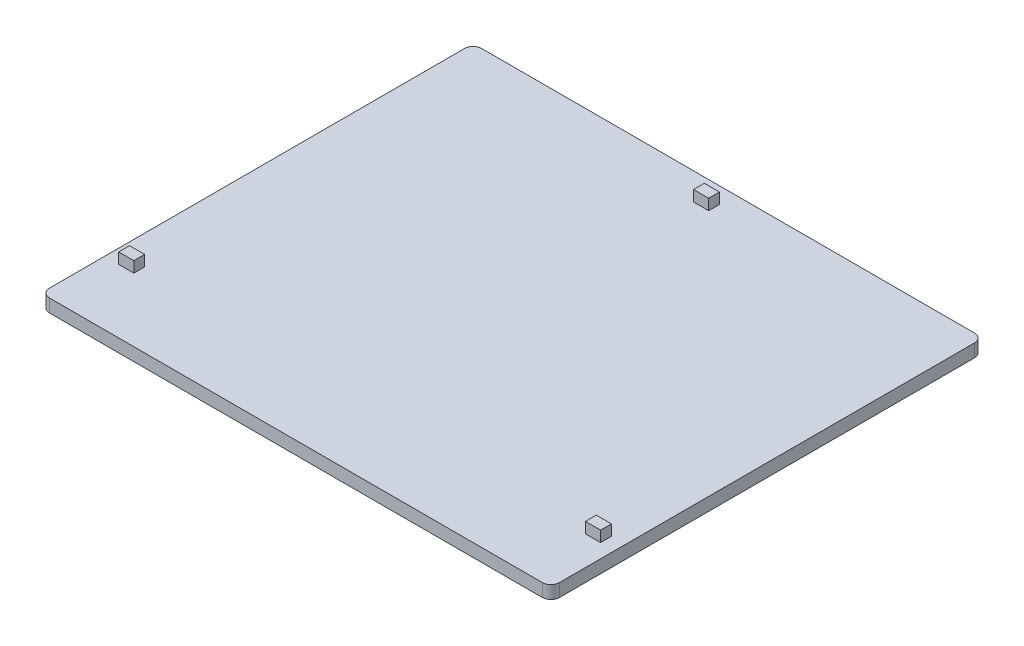
SolidWorks part; units mm, degrees
ref_plane "Front Plane" through (0, 0, 0) normal (0, 0, 1) x (1, 0, 0)
ref_plane "Top Plane" through (0, 0, 0) normal (0, 1, 0) x (1, 0, 0)
ref_plane "Right Plane" through (0, 0, 0) normal (1, 0, 0) x (0, 0, -1)
sketch "Sketch1" plane through (0, 0, 0) normal (0, 1, 0) x (1, 0, 0)
  line L1 (-59, 50) -> (59, 50)
  line L2 (-59, 50) -> (-59, -50)
  line L3 (-59, -50) -> (59, -50)
  line L4 (59, 50) -> (59, -50)
  line L5 (-59, 50) -> (59, -50) construction
  line L6 (-59, -50) -> (59, 50) construction
  point P0 (0, 0)
  dimension "D1" = 118
  dimension "D2" = 100
extrude "Boss-Extrude1" add sketch "Sketch1" along normal blind 3
fillet "Fillet1" radius 2 4 edges at (-59, 1.5, -50) (59, 1.5, -50) (59, 1.5, 50) (-59, 1.5, 50)
sketch "Sketch2" plane through (0, 3, 0) normal (0, 1, 0) x (1, 0, 0)
  line L0 (-59, -34) -> (59, -34) construction
  line L1 (-59, 48) -> (-59, -48) construction
  line L2 (59, -48) -> (59, 48) construction
  line L3 (-57, -50) -> (57, -50) construction
  line L4 (0, 50) -> (0, -50) construction
  line L5 (-55.75, -32.75) -> (-52.25, -32.75)
  line L6 (-55.75, -32.75) -> (-55.75, -35.25)
  line L7 (-55.75, -35.25) -> (-52.25, -35.25)
  line L8 (-52.25, -32.75) -> (-52.25, -35.25)
  line L9 (-55.75, -32.75) -> (-52.25, -35.25) construction
  line L10 (-55.75, -35.25) -> (-52.25, -32.75) construction
  line L11 (57, 50) -> (-57, 50) construction
  line L12 (55.75, -35.25) -> (52.25, -35.25)
  line L13 (52.25, -32.75) -> (52.25, -35.25)
  line L14 (55.75, -32.75) -> (52.25, -32.75)
  line L15 (55.75, -32.75) -> (55.75, -35.25)
  line L16 (-59, 45) -> (59, 45) construction
  line L18 (-1.75, 46.25) -> (1.75, 46.25)
  line L19 (-1.75, 46.25) -> (-1.75, 43.75)
  line L20 (-1.75, 43.75) -> (1.75, 43.75)
  line L21 (1.75, 46.25) -> (1.75, 43.75)
  line L22 (-1.75, 46.25) -> (1.75, 43.75) construction
  line L23 (-1.75, 43.75) -> (1.75, 46.25) construction
  point P8 (-54, -34)
  point P23 (0, 45)
  dimension "D1" = 16
  dimension "D2" = 2.5
  dimension "D3" = 3.5
  dimension "D4" = 5
  dimension "D5" = 5
extrude "Boss-Extrude2" add sketch "Sketch2" along normal blind 2.5
